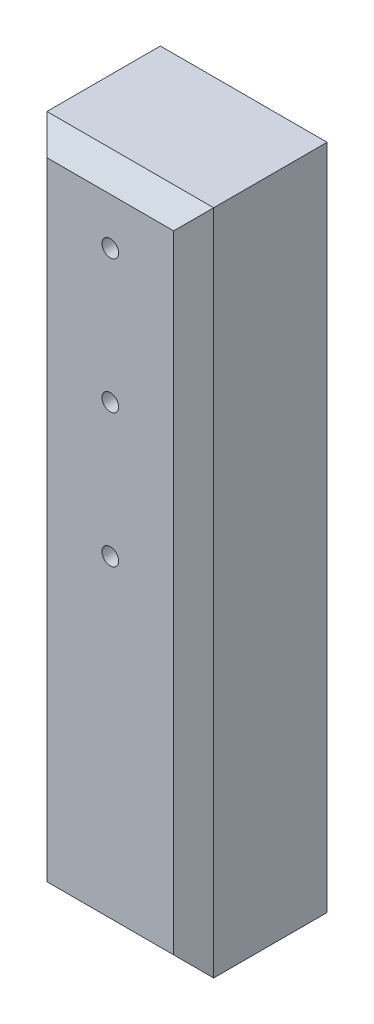
SolidWorks part; units mm, degrees
ref_plane "Front Plane" through (0, 0, 0) normal (0, 0, 1) x (1, 0, 0)
ref_plane "Top Plane" through (0, 0, 0) normal (0, 1, 0) x (1, 0, 0)
ref_plane "Right Plane" through (0, 0, 0) normal (1, 0, 0) x (0, 0, -1)
sketch "Sketch1" plane through (0, 0, 0) normal (0, 1, 0) x (1, 0, 0)
  line L0 (-17.25, 10) -> (17.25, -10) construction
  line L1 (-17.25, -10) -> (17.25, -10)
  line L2 (-17.25, -10) -> (-17.25, 10)
  line L3 (-17.25, 10) -> (17.25, 10)
  line L5 (-17.25, -10) -> (17.25, 10) construction
  line L6 (-17.25, 10) -> (17.25, -10) construction
  line L7 (-5, 5) -> (13, -5) construction
  line L8 (-5, -5) -> (13, 5) construction
  line L9 (4, 0) -> (25.25, 0) construction
  line L10 (4, 0) -> (-17.25, 0) construction
  line L12 (17.25, 10) -> (25.25, 10)
  line L14 (17.25, -10) -> (25.25, -10)
  line L15 (25.25, 10) -> (25.25, -10)
  circle A0 centre (-5, 5) radius 1.6
  arc A1 (-4.7872, -6.5858) -> (-5.2128, -6.5858) centre (-5, -5) ccw construction
  arc A2 (13.2128, -6.5858) -> (12.7872, -6.5858) centre (13, -5) ccw construction
  circle A3 centre (13, 5) radius 1.6
  circle A4 centre (-14, 4.0819) radius 1.625 construction
  circle A5 centre (-14, -4.0819) radius 1.625 construction
  circle A6 centre (-9.6025, 0) radius 1.6 construction
  circle A7 centre (-5, -5) radius 1.6
  circle A8 centre (13, -5) radius 1.6
  point P2 (0, 0)
  point P23 (4, 0)
  dimension "D1" = 21.25
extrude "Boss-Extrude1" add sketch "Sketch1" along normal blind 100
sketch "Sketch2" plane through (0, 0, 0) normal (0, -1, 0) x (1, 0, 0)
  line L0 (-5, 5) -> (13, -5) construction
  line L1 (-5, -5) -> (13, 5) construction
  line L2 (25.25, -10) -> (-17.25, -10) construction
  line L3 (16.5, 10) -> (-8.5, 10) construction
  line L4 (16.5, 10) -> (16.5, -10) construction
  line L5 (16.5, -10) -> (-8.5, -10) construction
  line L6 (-8.5, 10) -> (-8.5, -10) construction
  line L7 (16.5, 10) -> (-8.5, -10) construction
  line L8 (16.5, -10) -> (-8.5, 10) construction
  line L10 (-8.5, 10) -> (-17.25, 10)
  line L11 (-8.5, 10) -> (-8.5, -10)
  line L12 (-8.5, -10) -> (-17.25, -10)
  line L13 (-17.25, 10) -> (-17.25, -10)
  line L14 (16.5, 10) -> (25.25, 10)
  line L15 (16.5, 10) -> (16.5, -10)
  line L16 (16.5, -10) -> (25.25, -10)
  line L17 (25.25, 10) -> (25.25, -10)
  point P8 (4, 0)
  dimension "D1" = 25
extrude "Cut-Extrude1" cut sketch "Sketch2" against normal blind 100
sketch "Sketch3" plane through (0, 100, 0) normal (0, 1, 0) x (1, 0, 0)
  line L4 (16.5, 10) -> (-8.5, 10)
  line L5 (-8.5, 10) -> (-8.5, -10)
  line L6 (-8.5, -10) -> (16.5, -10)
  line L7 (16.5, -10) -> (16.5, 10)
  line L8 (16.5, 10) -> (-8.5, 10)
  line L9 (-8.5, 10) -> (-8.5, -10)
  line L10 (-8.5, -10) -> (16.5, -10)
  line L11 (16.5, -10) -> (16.5, 10)
  dimension "D1" = 0
extrude "Boss-Extrude2" add sketch "Sketch3" against normal blind 60
sketch "Sketch4" plane through (0, 0, 10) normal (0, 0, 1) x (1, 0, 0)
  line L0 (4, 100) -> (4, 0) construction
  line L1 (-8.5, 100) -> (16.5, 100) construction
  line L2 (-8.5, 0) -> (16.5, 0) construction
  line L3 (4, 70) -> (4, 50) construction
  line L4 (4, 90) -> (4, 70) construction
  circle A0 centre (4, 50) radius 1.25
  circle A1 centre (4, 70) radius 1.25
  circle A2 centre (4, 90) radius 1.25
  dimension "D1" = 2.5
  dimension "D2" = 2.5
  dimension "D3" = 2.5
  dimension "D4" = 20
  dimension "D5" = 20
extrude "Cut-Extrude2" cut sketch "Sketch4" against normal blind 60
sketch "Sketch5" plane through (0, 0, 10) normal (0, 0, 1) x (1, 0, 0)
  line L0 (4, 100) -> (4, 90) construction
  line L1 (-8.5, 100) -> (16.5, 100) construction
  line L2 (4, 90) -> (4, 70) construction
  line L3 (4, 70) -> (4, 50) construction
  line L4 (4, 50) -> (4, 30) construction
  line L5 (4, 100) -> (24, 100)
  line L6 (24, 100) -> (24, 30)
  line L7 (24, 30) -> (4, 30)
  line L8 (4, 100) -> (-16, 100)
  line L9 (-16, 100) -> (-16, 30)
  line L10 (-16, 30) -> (4, 30)
  circle A0 centre (4, 90) radius 1.25
  circle A1 centre (4, 70) radius 1.25
  circle A2 centre (4, 50) radius 1.25
  dimension "D1" = 20
  dimension "D2" = 20
  dimension "D3" = 20
chamfer "Chamfer1" distance 3 angle 45 4 edges at (4, 0, 10) (16.5, 50, 10) (4, 100, 10) (-8.5, 50, 10)
